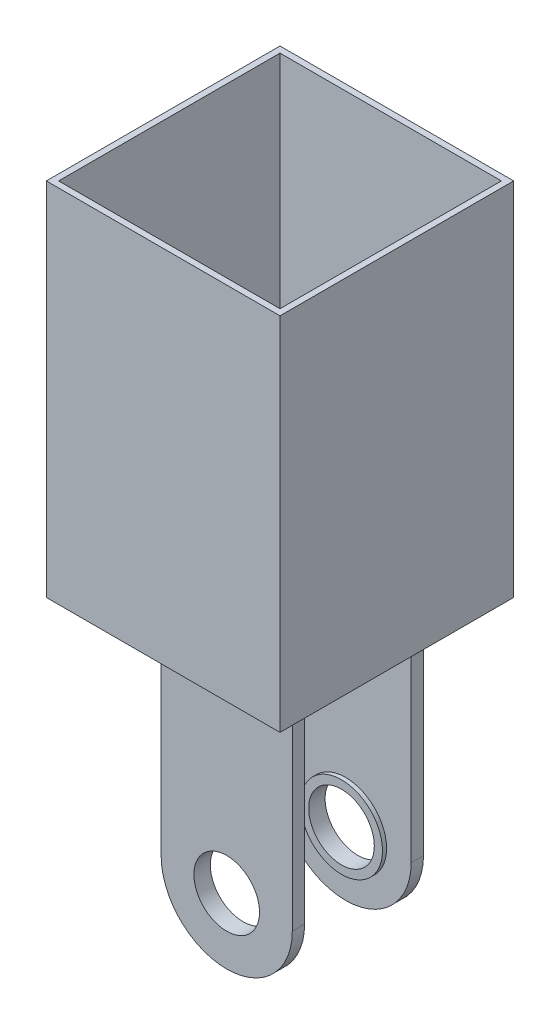
SolidWorks part; units mm, degrees
ref_plane "前视基准面" through (0, 0, 0) normal (0, 0, 1) x (1, 0, 0)
ref_plane "上视基准面" through (0, 0, 0) normal (0, 1, 0) x (1, 0, 0)
ref_plane "右视基准面" through (0, 0, 0) normal (1, 0, 0) x (0, 0, -1)
other "Configuration Table"
sketch "草图1" plane through (0, 0, 0) normal (0, 0, 1) x (1, 0, 0)
  line L2 (0, 0) -> (0, 56) construction
  line L3 (-16, -93.9082) -> (16, -93.9082)
  line L4 (-16, 0) -> (-16, 56)
  line L6 (16, 0) -> (16, 56)
  line L7 (-2.6873, -15.7727) -> (1.3437, 7.8864) construction
  line L8 (-1.3437, 7.8864) -> (2.6873, -15.7727) construction
  line L10 (-28.5, 56) -> (-28.5, 96)
  line L11 (28.5, 56) -> (28.5, 96)
  line L12 (-28.5, 96) -> (28.5, 96)
  line L13 (0, 56) -> (28.5, 96) construction
  line L14 (-16, 56) -> (-28.5, 56)
  line L15 (16, 56) -> (28.5, 56)
  line L17 (0, 56) -> (-28.5, 96) construction
  circle A0 centre (0, 0) radius 8
  arc A3 (-16, 0) -> (16, 0) centre (0, 0) ccw
extrude "凸台-拉伸1" add sketch "草图1" along normal blind 3 contours L4 A3 L6 L15 L11 L12 L10 L14 A0
sketch "草图2" plane through (0, 0, 3) normal (0, 0, 1) x (1, 0, 0)
  circle A0 centre (0, 0) radius 10
  circle A1 centre (0, 0) radius 8 construction
  circle A2 centre (0, 0) radius 8
extrude "凸台-拉伸3" add sketch "草图2" along normal blind 1
ref_plane "基准面1" through (0, 0, 29) normal (0, 0, 1) x (1, 0, 0)
sketch "草图4" plane through (0, 0, 29) normal (0, 0, 1) x (1, 0, 0)
  line L0 (-16, 0) -> (-16, 56)
  line L1 (-28.5, 56) -> (-28.5, 96)
  line L2 (28.5, 96) -> (28.5, 56)
  line L3 (16, 56) -> (16, 0)
  line L7 (-16, 56) -> (-16, 0)
  line L8 (16, 0) -> (16, 56)
  line L9 (16, 56) -> (28.5, 56)
  line L10 (28.5, 56) -> (28.5, 96)
  line L11 (28.5, 96) -> (-28.5, 96)
  line L12 (-28.5, 96) -> (-28.5, 56)
  line L13 (-28.5, 56) -> (-16, 56)
  line L14 (-16, 56) -> (-16, 0)
  line L15 (16, 0) -> (16, 56)
  line L16 (16, 56) -> (28.5, 56)
  line L17 (28.5, 56) -> (28.5, 96)
  line L18 (28.5, 96) -> (-28.5, 96)
  line L19 (-28.5, 96) -> (-28.5, 56)
  line L20 (-28.5, 56) -> (-16, 56)
  arc A0 (-16, 0) -> (16, 0) centre (0, 0) ccw
  arc A1 (-16, 0) -> (16, 0) centre (0, 0) ccw
  arc A2 (-16, 0) -> (16, 0) centre (0, 0) ccw
  circle A3 centre (0, 0) radius 8
  dimension "D1" = 0
extrude "凸台-拉伸4" add sketch "草图4" along normal blind 3 separate body contours L0 A0 L3 L16 L2 L18 L1 L20 A3
sketch "草图5" plane through (0, 0, 29) normal (0, 0, -1) x (-1, 0, 0)
  circle A0 centre (0, 0) radius 10
  circle A1 centre (0, 0) radius 8
extrude "凸台-拉伸5" add sketch "草图5" along normal blind 1
sketch "草图6" plane through (0, 56, 0) normal (0, -1, 0) x (1, 0, 0)
  line L0 (16, 3) -> (-16, 3) construction
  line L5 (-28.5, 31.5753) -> (28.5, -25.5753) construction
  line L6 (-28.5, -25.5753) -> (28.5, 31.5753) construction
  line L7 (0, 28) -> (0, 10) construction
  line L9 (-10, 28) -> (10, 28) construction
  line L10 (0, 10) -> (0, 3) construction
  line L12 (-28.5, 47.5) -> (28.5, 47.5)
  line L13 (-28.5, 47.5) -> (-28.5, -9.5)
  line L14 (-28.5, -9.5) -> (28.5, -9.5)
  line L15 (28.5, 47.5) -> (28.5, -9.5)
  line L16 (-28.5, 47.5) -> (28.5, -9.5) construction
  line L17 (-28.5, -9.5) -> (28.5, 47.5) construction
  point P0 (0, 3)
  point P12 (0, 19)
extrude "凸台-拉伸6" add sketch "草图6" against normal blind 3
sketch "草图9" plane through (0, 56, 0) normal (0, -1, 0) x (1, 0, 0)
  line L0 (-28.5, 47.5) -> (28.5, -9.5) construction
  line L1 (28.5, 47.5) -> (-28.5, -9.5)
  circle A0 centre (0, 19) radius 7.25
extrude "切除-拉伸1" cut sketch "草图9" against normal blind 5 contours A0 L0 L1 | L1 L0 A0 | L0 L1 A0 | L0 A0 L1
sketch "草图10" plane through (0, 59, 0) normal (0, 1, 0) x (1, 0, 0)
  line L4 (-28.5, -29) -> (28.5, -29)
  line L5 (28.5, -29) -> (28.5, -3)
  line L6 (28.5, -3) -> (-28.5, -3)
  line L7 (-28.5, -3) -> (-28.5, -29)
  line L8 (-28.5, -29) -> (28.5, -29)
  line L9 (28.5, -29) -> (28.5, -3)
  line L10 (28.5, -3) -> (-28.5, -3)
  line L11 (-28.5, -3) -> (-28.5, -29)
  circle A0 centre (0, -19) radius 7.25 construction
  circle A1 centre (0, -19) radius 7.25
  circle A2 centre (0, -19) radius 8.25
  circle M5 centre (0, -19) radius 7.25
  dimension "D1" = 0
extrude "凸台-拉伸7" add sketch "草图10" along normal blind 2 contours A2 M5
sketch "草图11" plane through (-28.5, 0, 0) normal (-1, 0, 0) x (0, 0, 1)
  line L1 (0, 96) -> (32, 96)
  line L2 (0, 96) -> (0, 59)
  line L3 (0, 59) -> (32, 59)
  line L4 (32, 96) -> (32, 59)
extrude "切除-拉伸2" cut sketch "草图11" against normal blind 57
sketch "草图12" plane through (0, 59, 0) normal (0, 1, 0) x (1, 0, 0)
  line L0 (-28.5, 9.5) -> (28.5, -47.5) construction
  line L1 (-28.5, 9.5) -> (28.5, 9.5)
  line L2 (-28.5, 9.5) -> (-28.5, -47.5)
  line L3 (-28.5, -47.5) -> (28.5, -47.5)
  line L4 (28.5, 9.5) -> (28.5, -47.5)
  line L5 (28.5, 9.5) -> (-28.5, -47.5) construction
  line L7 (-27, 8) -> (27, 8)
  line L8 (-27, 8) -> (-27, -46)
  line L9 (-27, -46) -> (27, -46)
  line L10 (27, 8) -> (27, -46)
  line L11 (-27, 8) -> (27, -46) construction
  line L12 (-27, -46) -> (27, 8) construction
  point P6 (0, -19)
extrude "凸台-拉伸8" add sketch "草图12" along normal blind 85
